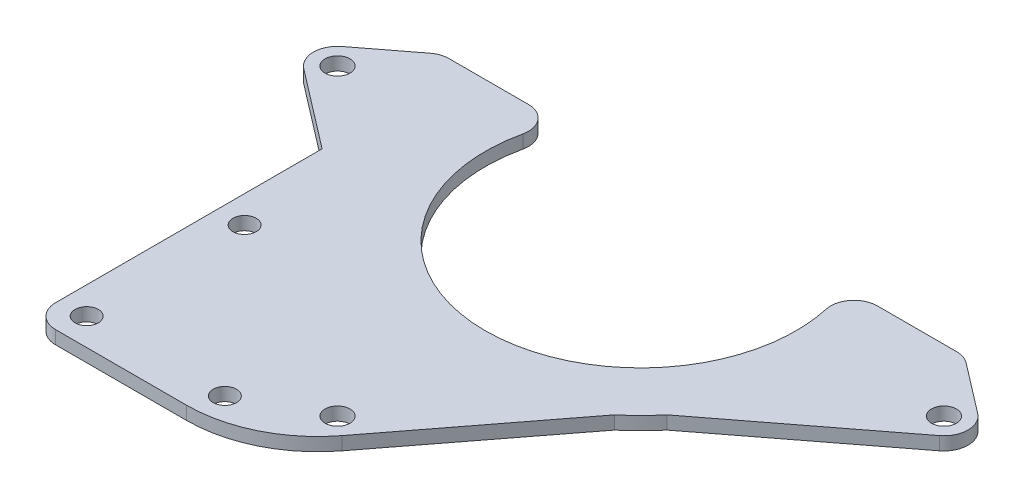
SolidWorks part; units mm, degrees
other "motor_mount" parameters "D1"=97.7653, "D2"=14.7748, "D5"=1.5153, "D6"=1.2729, "D7"=2.6145, "D8"=27.5115, "D9"=27.5368, "D10"=3, "D11"=7.957, "D12"=2, "D14"=6.8142, "D15"=5.6048, "D3"=9, "D4"=4.1559, "D13"=13.0555
ref_plane "Front Plane" through (0, 0, 0) normal (0, 0, 1) x (1, 0, 0)
ref_plane "Top Plane" through (0, 0, 0) normal (0, 1, 0) x (1, 0, 0)
ref_plane "Right Plane" through (0, 0, 0) normal (1, 0, 0) x (0, 0, -1)
sketch "Sketch1" plane through (0, 0, 0) normal (0, 1, 0) x (1, 0, 0)
  line L0 (0, 0) -> (0, 9) construction
  line L1 (0, 0) -> (7.7942, -4.5) construction
  line L3 (-2.4599, -40.9065) -> (-17.6737, -21.0687)
  line L4 (0, 0) -> (39.02, 0) construction
  line L5 (17.6737, -21.0687) -> (2.4599, -40.9065)
  line L6 (-40.9065, 2.4599) -> (-21.0687, 17.6737)
  line L7 (21.0687, 17.6737) -> (40.9065, 2.4599)
  line L8 (40.9065, -2.4599) -> (21.0687, -17.6737)
  line L9 (-21.0687, -17.6737) -> (-40.9065, -2.4599)
  line L10 (2.4599, 40.9065) -> (17.6737, 21.0687)
  line L11 (-17.6737, 21.0687) -> (-2.4599, 40.9065)
  line L12 (0, 0) -> (21.0687, 17.6737) construction
  circle A0 centre (0, 0) radius 27.5 construction
  circle A8 centre (39.02, 0) radius 1.6
  circle A9 centre (0, 0) radius 20
  arc A11 (40.9065, -2.4599) -> (40.9065, 2.4599) centre (39.02, 0) ccw
  circle A12 centre (0, 0) radius 27.5
  arc A14 (-2.4599, -40.9065) -> (2.4599, -40.9065) centre (0, -39.02) ccw
  circle A16 centre (0, -39.02) radius 1.6
  arc A18 (-40.9065, 2.4599) -> (-40.9065, -2.4599) centre (-39.02, 0) ccw
  circle A19 centre (-39.02, 0) radius 1.6
  arc A20 (2.4599, 40.9065) -> (-2.4599, 40.9065) centre (0, 39.02) ccw
  circle A21 centre (0, 39.02) radius 1.6
  dimension "D1" = 55
  dimension "D11" = 40
  dimension "D12" = 3.2
  dimension "D3" = 120
  dimension "D13" = 39.02
  dimension "D15" = 1.5
  dimension "D5" = 25
  dimension "D8" = 27.5
  dimension "D9" = 21.0687
  dimension "D6" = 4
extrude "Boss-Extrude2" add sketch "Sketch1" along normal blind 1.7
sketch "Sketch2" plane through (0, 1.7, 0) normal (0, 1, 0) x (1, 0, 0)
  line L1 (-30.78, -47.52) -> (-30.78, -10.226)
  line L2 (-21.0687, -17.6737) -> (-40.9065, -2.4599) construction
  line L3 (-2.4599, -40.9065) -> (-17.6737, -21.0687) construction
  line L4 (-2.4599, -40.9065) -> (-17.6737, -21.0687)
  line L5 (-21.0687, -17.6737) -> (-30.78, -10.226)
  line L6 (-30.78, -47.52) -> (-10.9465, -47.52)
  arc A0 (-2.4599, -40.9065) -> (2.4599, -40.9065) centre (0, -39.02) ccw construction
  arc A1 (-21.0687, -17.6737) -> (-17.6737, -21.0687) centre (0, 0) ccw construction
  arc A2 (-21.0687, -17.6737) -> (-17.6737, -21.0687) centre (0, 0) ccw
  arc A3 (-2.4599, -40.9065) -> (2.4599, -40.9065) centre (0, -39.02) ccw
  circle A4 centre (-9.5, -44.02) radius 1.5
  arc A6 (2.4599, -40.9065) -> (-10.9465, -47.52) centre (-10.9465, -30.625) cw
  circle A7 centre (-27.28, -44.02) radius 1.5
  circle A8 centre (-27.28, -23.7) radius 1.5
  point P4 (0, 0)
  dimension "D1" = 5
  dimension "D2" = 3
  dimension "D3" = 3.5
  dimension "D4" = 9.5
  dimension "D5" = 17.78
  dimension "D6" = 3.5
  dimension "D7" = 20.32
extrude "Boss-Extrude3" add sketch "Sketch2" against normal blind 1.7
sketch "Sketch3" plane through (0, 1.7, 0) normal (0, 1, 0) x (1, 0, 0)
  line L0 (-40.9065, 2.4599) -> (-21.0687, 17.6737) construction
  line L1 (-33.6826, 8) -> (33.6826, 8)
  line L2 (-33.6826, 8) -> (-33.6826, 44)
  line L3 (-33.6826, 44) -> (33.6826, 44)
  line L4 (33.6826, 8) -> (33.6826, 44)
  line L5 (21.0687, 17.6737) -> (40.9065, 2.4599) construction
  circle A0 centre (-39.02, 0) radius 1.6 construction
  point P6 (36.2218, 6.0526)
  dimension "D1" = 8
  dimension "D2" = 36
extrude "Cut-Extrude1" cut sketch "Sketch3" against normal blind 1.7
fillet "Fillet1" radius 3 5 edges at (-30.78, 0.85, 47.52) (33.6826, 0.85, -8) (-18.3303, 0.85, -8) (18.3303, 0.85, -8) (-33.6826, 0.85, -8)
equation "\"Hwidth\"= 39.02"
equation "\"D13@Sketch1\"=\"Hwidth\""
equation "\"Mdia\"=2.3"
equation "\"Shaft\"=40"
equation "\"D11@Sketch1\"=\"Shaft\""
equation "\"Mounthole\"=3.2"
equation "\"D12@Sketch1\"=\"Mounthole\""
equation "\"MainDia\"=55"
equation "\"D1@Sketch1\"=\"MainDia\""
